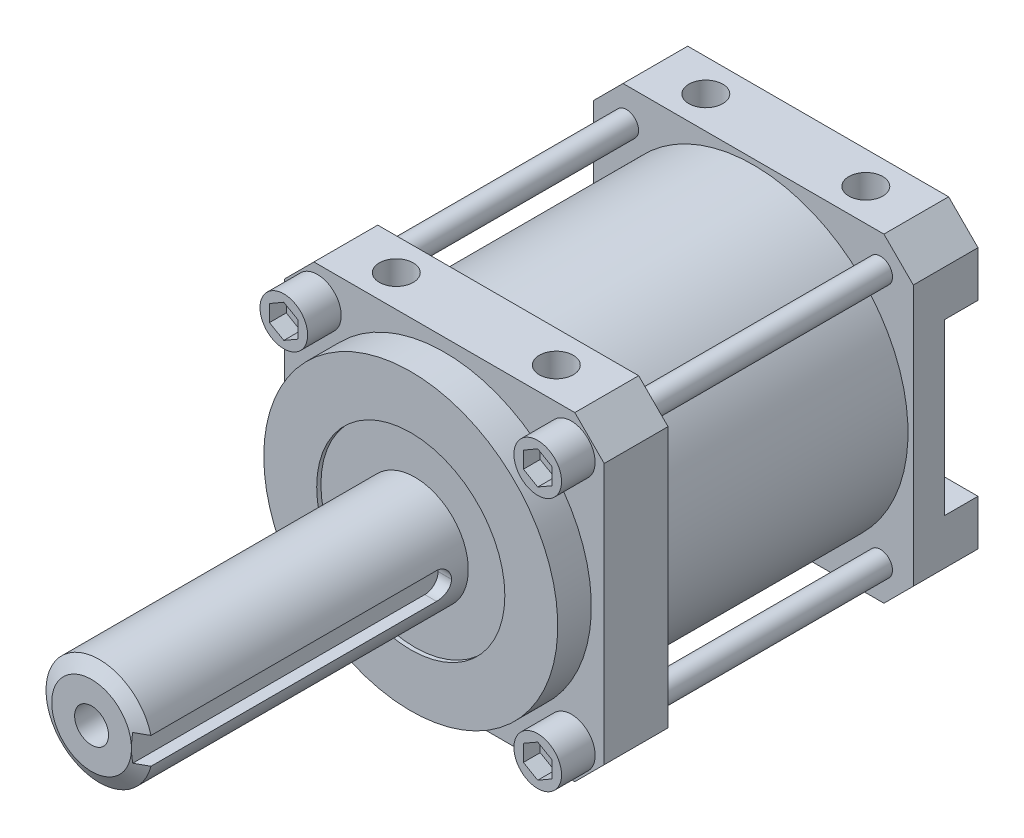
SolidWorks part; units mm, degrees
ref_plane "Plano frontal" through (0, 0, 0) normal (0, 0, 1) x (1, 0, 0)
ref_plane "Plano superior" through (0, 0, 0) normal (0, 1, 0) x (1, 0, 0)
ref_plane "Plano direito" through (0, 0, 0) normal (1, 0, 0) x (0, 0, -1)
sketch "Esboço2" plane through (0, 0, 0) normal (0, 0, 1) x (1, 0, 0)
  line L0 (-19.03, 15.53) -> (-15.53, 19.03)
  line L1 (-15.53, 19.03) -> (15.53, 19.03)
  line L2 (-19.03, 15.53) -> (-19.03, -15.53)
  line L3 (-15.53, -19.03) -> (15.53, -19.03)
  line L4 (19.03, 15.53) -> (19.03, -15.53)
  line L5 (-19.03, 19.03) -> (19.03, -19.03) construction
  line L6 (-19.03, -19.03) -> (19.03, 19.03) construction
  line L7 (15.53, 19.03) -> (19.03, 15.53)
  line L8 (15.53, -19.03) -> (19.03, -15.53)
  line L9 (-19.03, -15.53) -> (-15.53, -19.03)
  point P0 (0, 0)
  dimension "D1" = 38.06
extrude "Ressalto-extrusão1" add sketch "Esboço2" along normal blind 7.7
sketch "Esboço4" plane through (0, 0, 0) normal (0, 1, 0) x (1, 0, 0)
  line L0 (0, 5.7578) -> (0, -43.2819) construction
  line L1 (0, -7.7) -> (18.4, -7.7)
  line L2 (15.53, -7.7) -> (-15.53, -7.7) construction
  line L3 (18.4, -7.7) -> (18.4, -36.9)
  line L4 (18.4, -36.9) -> (0, -36.9)
  line L5 (0, -44.5) -> (17.5, -44.5)
  line L6 (17.5, -44.5) -> (17.5, -48.5)
  line L7 (17.5, -48.5) -> (11.2, -48.5)
  line L8 (11.2, -48.5) -> (11.2, -48)
  line L9 (11.2, -48) -> (6.35, -48)
  line L10 (6.35, -48) -> (6.35, -85.5762)
  line L11 (4.75, -86.5) -> (0, -86.5)
  line L12 (0, -7.7) -> (0, -36.9)
  line L13 (0, -44.5) -> (0, -86.5)
  line L14 (4.75, -86.5) -> (6.35, -85.5762)
  line L16 (15.53, 0) -> (-15.53, 0) construction
  dimension "D1" = 7.6
  dimension "D2" = 35
  dimension "D3" = 36.8
  dimension "D4" = 4
  dimension "D5" = 0.5
  dimension "D6" = 12.7
  dimension "D7" = 6.3
  dimension "D8" = 48.5
  dimension "D9" = 38.5
  dimension "D10" = 1.6
  dimension "D11" = 30
revolve "Revolução1" add sketch "Esboço4" angle 360 about L0
sketch "Esboço3" plane through (0, 0, 0) normal (0, 0, -1) x (-1, 0, 0)
  line L0 (-27.8012, 0) -> (24.2684, 0) construction
  line L1 (0, 20.0829) -> (0, -20.7741) construction
  circle A0 centre (0, 0) radius 6.45
  dimension "D1" = 12.9
extrude "Corte-extrusão1" cut sketch "Esboço3" against normal blind 9.9
sketch "Esboço5" plane through (0, 0, 36.9) normal (0, 0, 1) x (1, 0, 0)
  line L8 (-15.53, 19.03) -> (-19.03, 15.53)
  line L9 (15.53, 19.03) -> (-15.53, 19.03)
  line L10 (19.03, 15.53) -> (15.53, 19.03)
  line L11 (19.03, -15.53) -> (19.03, 15.53)
  line L12 (15.53, -19.03) -> (19.03, -15.53)
  line L13 (-15.53, -19.03) -> (15.53, -19.03)
  line L14 (-19.03, -15.53) -> (-15.53, -19.03)
  line L15 (-19.03, 15.53) -> (-19.03, -15.53)
  line L16 (-15.53, 19.03) -> (-19.03, 15.53)
  line L17 (15.53, 19.03) -> (-15.53, 19.03)
  line L18 (19.03, 15.53) -> (15.53, 19.03)
  line L19 (19.03, -15.53) -> (19.03, 15.53)
  line L20 (15.53, -19.03) -> (19.03, -15.53)
  line L21 (-15.53, -19.03) -> (15.53, -19.03)
  line L22 (-19.03, -15.53) -> (-15.53, -19.03)
  line L23 (-19.03, 15.53) -> (-19.03, -15.53)
  dimension "D1" = 0
extrude "Ressalto-extrusão2" add sketch "Esboço5" along normal up to surface (7.6 mm away) up to face at (-17.5, 0, 44.5)
sketch "Esboço6" plane through (0, 0, 0) normal (0, 0, -1) x (-1, 0, 0)
  line L0 (-23.9277, 0) -> (27.7135, 0) construction
  line L1 (0, -26.31) -> (0, 25.2771) construction
  line L2 (-19.03, -10.1) -> (-19.03, 10.1)
  line L4 (-19.03, -15.53) -> (-19.03, 15.53) construction
  line L5 (-19.03, 10.1) -> (-9.0127, 10.1)
  line L6 (-19.03, -10.1) -> (-9.0127, -10.1)
  line L7 (19.03, -10.1) -> (9.0127, -10.1)
  line L8 (19.03, 10.1) -> (9.0127, 10.1)
  line L9 (19.03, -10.1) -> (19.03, 10.1)
  line L10 (-5.75, -14.6227) -> (-5.75, -10.9658) construction
  line L11 (5.75, -14.6227) -> (5.75, -12.951) construction
  arc A1 (-9.0127, 10.1) -> (-6.4133, 4.8653) centre (-9.0127, 6.8373) cw
  circle A2 centre (0, 0) radius 8.05
  arc A3 (6.4133, -4.8653) -> (6.4133, 4.8653) centre (0, 0) ccw
  arc A4 (-9.0127, -10.1) -> (-6.4133, -4.8653) centre (-9.0127, -6.8373) ccw
  arc A5 (9.0127, -10.1) -> (6.4133, -4.8653) centre (9.0127, -6.8373) cw
  arc A6 (9.0127, 10.1) -> (6.4133, 4.8653) centre (9.0127, 6.8373) ccw
  arc A7 (-6.4133, 4.8653) -> (-6.4133, -4.8653) centre (0, 0) ccw
  point P19 (-19.03, 0)
  point P25 (19.03, 0)
  dimension "D2" = 20.2
  dimension "D3" = 11.5
  dimension "D1" = 1.6
extrude "Corte-extrusão2" cut sketch "Esboço6" against normal blind 4
hole_wizard "Broca de rosquear para tarraxa de #10-321" positions "Esboço8" profile "Esboço7" hole size "#10-32" standard "Ansi Inch"
sketch "Esboço8" plane through (0, 0, 86.5) normal (0, 0, 1) x (1, 0, 0)
  point P0 (0, 0)
sketch "Esboço7" plane through (0, 0, 86.5) normal (1, 0, 0) x (0, -1, 0)
  line L0 (0, 0) -> (0, 8.8333)
  line L1 (0, 8.8333) -> (2.0193, 7.62)
  line L2 (2.0193, 7.62) -> (2.0193, 0)
  line L5 (2.0193, 0) -> (0, 0)
  line L10 (0, 8.8333) -> (-2.0193, 7.62) construction
  line L11 (0, -6.35) -> (0, 107.95) construction
  dimension "Hole Dia." = 4.0386
  dimension "Hole Depth" = 7.62
  dimension "Drill Angle" = 118
sketch "Esboço9" plane through (0, 0, 86.5) normal (0, 0, 1) x (1, 0, 0)
  line L0 (4.75, 1.5875) -> (4.75, -1.5875)
  line L1 (4.75, -1.5875) -> (6.5456, -1.5875)
  line L2 (6.5456, -1.5875) -> (6.5456, 1.5875)
  line L3 (6.5456, 1.5875) -> (4.75, 1.5875)
  line L4 (-25.958, 0) -> (25.8044, 0) construction
  circle A0 centre (0, 0) radius 4.75 construction
  dimension "D1" = 3.175
extrude "Corte-extrusão3" cut sketch "Esboço9" against normal blind 36.5
fillet "Filete1" radius 1.58 2 edges at (5.4492, -1.5875, 50) (5.4492, 1.5875, 50)
sketch "Esboço10 - Posicionamento de furos" plane through (0, 19.03, 0) normal (0, 1, 0) x (1, 0, 0)
  line L0 (-15.53, -3.85) -> (28.7085, -3.85) construction
  line L1 (-15.53, -7.7) -> (-15.53, 0) construction
  line L2 (-15.53, -40.7) -> (24.0604, -40.7) construction
  line L3 (-15.53, -44.5) -> (-15.53, -36.9) construction
  line L4 (0, 7.8221) -> (0, -64.1576) construction
  line L5 (9.525, -1.2086) -> (9.525, -61.4005) construction
  line L6 (-9.525, -1.2086) -> (-9.525, -61.4005) construction
  dimension "D1" = 9.525
hole_wizard "Broca de rosquear para tarraxa de #10-322" positions "Esboço12" profile "Esboço11" hole size "#10-32" standard "Ansi Inch"
sketch "Esboço12" plane through (0, 19.03, 0) normal (0, 1, 0) x (1, 0, 0)
  line L0 (-15.53, -3.85) -> (28.7085, -3.85) construction
  line L1 (9.525, -1.2086) -> (9.525, -61.4005) construction
  line L2 (-9.525, -1.2086) -> (-9.525, -61.4005) construction
  line L3 (-15.53, -40.7) -> (24.0604, -40.7) construction
  point P0 (9.525, -3.85)
  point P6 (-9.525, -3.85)
  point P10 (-9.525, -40.7)
  point P14 (9.525, -40.7)
sketch "Esboço11" plane through (9.525, 19.03, 3.85) normal (1, 0, 0) x (0, 0, 1)
  line L0 (0, 0) -> (0, 8.8333)
  line L1 (0, 8.8333) -> (2.0193, 7.62)
  line L2 (2.0193, 7.62) -> (2.0193, 0)
  line L5 (2.0193, 0) -> (0, 0)
  line L10 (0, 8.8333) -> (-2.0193, 7.62) construction
  line L11 (0, -6.35) -> (0, 107.95) construction
  dimension "Hole Dia." = 4.0386
  dimension "Hole Depth" = 7.62
  dimension "Drill Angle" = 118
mirror "Espelhar3" about plane through (0, 0, 0) normal (0, 1, 0) of "Broca de rosquear para tarraxa de #10-322"
sketch "Esboço13 - Posicionamento de furo" plane through (0, 0, 0) normal (0, 0, -1) x (-1, 0, 0)
  line L0 (0, 20.4669) -> (0, -21.3117) construction
  line L1 (-21.9644, 0) -> (24.8828, 0) construction
  circle A0 centre (-15.115, 15.115) radius 1.4592
  circle A1 centre (-15.115, -15.115) radius 1.4592
  circle A2 centre (15.115, -15.115) radius 1.4592
  circle A3 centre (15.115, 15.115) radius 1.4592
  dimension "D1" = 30.23
  dimension "D2" = 30.23
hole_wizard "Broca de rosquear para tarraxa de #6-401" positions "Esboço15" profile "Esboço14" hole size "#6-40" standard "Ansi Inch" end condition through all
sketch "Esboço15" plane through (0, 0, 0) normal (0, 0, -1) x (-1, 0, 0)
  point P0 (-15.115, 15.115)
  point P3 (15.115, 15.115)
  point P6 (15.115, -15.115)
  point P9 (-15.115, -15.115)
sketch "Esboço14" plane through (15.115, 15.115, 0) normal (1, 0, 0) x (0, 1, 0)
  line L0 (0, 0) -> (0, 86.5)
  line L1 (0, 86.5) -> (1.4351, 86.5)
  line L2 (1.4351, 86.5) -> (1.4351, 0)
  line L5 (1.4351, 0) -> (0, 0)
  line L11 (0, -6.35) -> (0, 107.95) construction
  dimension "Thru Hole Dia." = 2.8702
  dimension "Thru Hole Depth" = 86.5
ref_plane "Plano1" through (0, 15.115, 0) normal (0, 1, 0) x (1, 0, 0)
sketch "Esboço16" plane through (0, 15.115, 0) normal (0, 1, 0) x (1, 0, 0)
  line L0 (15.115, -60.9996) -> (15.115, 3.7689) construction
  line L1 (15.115, 0.5) -> (16.5501, 0.5)
  line L2 (16.5501, 0.5) -> (16.5501, -44.5)
  line L3 (16.5501, -44.5) -> (17.95, -44.5)
  line L4 (17.95, -44.5) -> (17.95, -48.5)
  line L5 (17.95, -48.5) -> (15.115, -48.5)
  line L6 (15.115, -48.5) -> (15.115, 0.5)
  line L7 (16.5501, 0) -> (13.6799, 0) construction
  line L8 (16.5501, 0) -> (13.6799, 0) construction
  line L9 (9.0127, 0) -> (19.03, 0) construction
  line L10 (15.53, -44.5) -> (19.03, -44.5) construction
  line L11 (15.53, -44.5) -> (19.03, -44.5) construction
  line L12 (-17.5, -48.5) -> (17.5, -48.5) construction
  line L13 (-17.5, -48.5) -> (17.5, -48.5) construction
  dimension "D1" = 0.5
  dimension "D2" = 5.67
revolve "Revolução2" add sketch "Esboço16" angle 360 about L0
sketch "Esboço17" plane through (0, 0, 48.5) normal (0, 0, 1) x (1, 0, 0)
  line L1 (13.4102, 16.0993) -> (13.4102, 14.1307)
  line L2 (13.4102, 14.1307) -> (15.115, 13.1465)
  line L3 (15.115, 13.1465) -> (16.8198, 14.1307)
  line L4 (16.8198, 14.1307) -> (16.8198, 16.0993)
  line L5 (16.8198, 16.0993) -> (15.115, 17.0835)
  line L6 (15.115, 17.0835) -> (13.4102, 16.0993)
  circle A0 centre (15.115, 15.115) radius 1.7048 construction
extrude "Corte-extrusão4" cut sketch "Esboço17" against normal offset from surface (2 mm away) 2 up to face at (17.95, 15.115, 44.5)
mirror "Espelhar2" about plane through (0, 0, 0) normal (1, 0, 0) of "Revolução2", "Corte-extrusão4"
mirror "Espelhar1" about plane through (0, 0, 0) normal (0, 1, 0) of "Espelhar2", "Revolução2", "Corte-extrusão4"
sketch "Esboço18 - Posicionamento Parafuso" plane through (0, 0, 7.7) normal (0, 0, -1) x (-1, 0, 0)
  line L0 (0, 20.1597) -> (0, -21.0045) construction
  line L1 (-22.7324, 0) -> (27.6476, 0) construction
  circle A0 centre (0, -12.5) radius 1.5551
  circle A1 centre (0, 12.5) radius 1.5551
  dimension "D1" = 25
hole_wizard "Escareado para parafuso de máquina com cabeça chata de #51" positions "Esboço20" profile "Esboço19" countersink size "#5" standard "Ansi Inch"
sketch "Esboço20" plane through (0, 0, 7.7) normal (0, 0, 1) x (1, 0, 0)
  point P0 (0, 12.5)
  point P3 (0, -12.5)
sketch "Esboço19" plane through (0, 12.5, 7.7) normal (1, 0, 0) x (0, -1, 0)
  line L0 (0, 0) -> (0, 8.2)
  line L1 (0, 8.2) -> (1.6319, 8.2)
  line L2 (1.6319, 8.2) -> (1.6319, 1.8043)
  line L3 (1.6319, 1.8043) -> (3.2004, 0)
  line L5 (3.2004, 0) -> (0, 0)
  line L6 (-1.6319, 1.8043) -> (-3.2004, 0) construction
  line L11 (0, -6.35) -> (0, 107.95) construction
  dimension "Thru Hole Dia." = 3.2639
  dimension "Thru Hole Depth" = 8.2
  dimension "Near C'Sink Dia." = 6.4008
  dimension "Near C'Sink Angle" = 82
